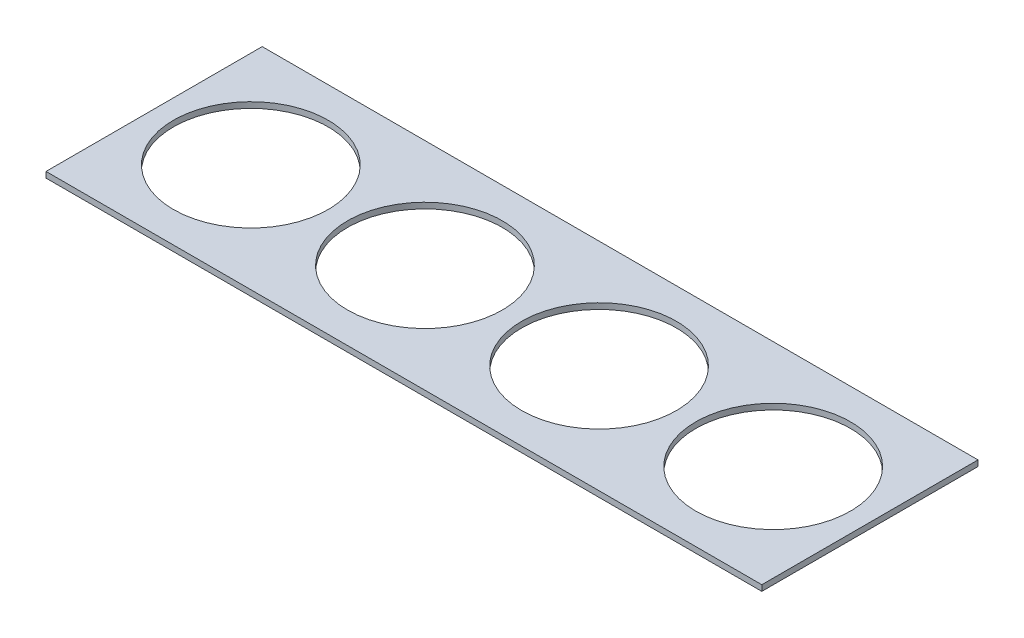
SolidWorks part; units mm, degrees
ref_plane "Front Plane" through (0, 0, 0) normal (0, 0, 1) x (1, 0, 0)
ref_plane "Top Plane" through (0, 0, 0) normal (0, 1, 0) x (1, 0, 0)
ref_plane "Right Plane" through (0, 0, 0) normal (1, 0, 0) x (0, 0, -1)
sketch "Sketch1" plane through (0, 0, 0) normal (0, 1, 0) x (1, 0, 0)
  line L1 (81.4621, 64.9352) -> (-288.5379, 64.9352)
  line L2 (81.4621, 64.9352) -> (81.4621, -46.8148)
  line L3 (81.4621, -46.8148) -> (-288.5379, -46.8148)
  line L4 (-288.5379, 64.9352) -> (-288.5379, -46.8148)
  circle A0 centre (-238.5379, 9.0602) radius 40
  circle A1 centre (-148.5379, 9.0602) radius 40
  circle A2 centre (-58.5379, 9.0602) radius 40
  circle A3 centre (31.4621, 9.0602) radius 40
  point P0 (0, 0)
  point P5 (-288.5379, 9.0602)
  dimension "D3" = 80
  dimension "D1" = 370
  dimension "D2" = 111.75
  dimension "D4" = 50
extrude "Boss-Extrude1" add sketch "Sketch1" along normal blind 3
